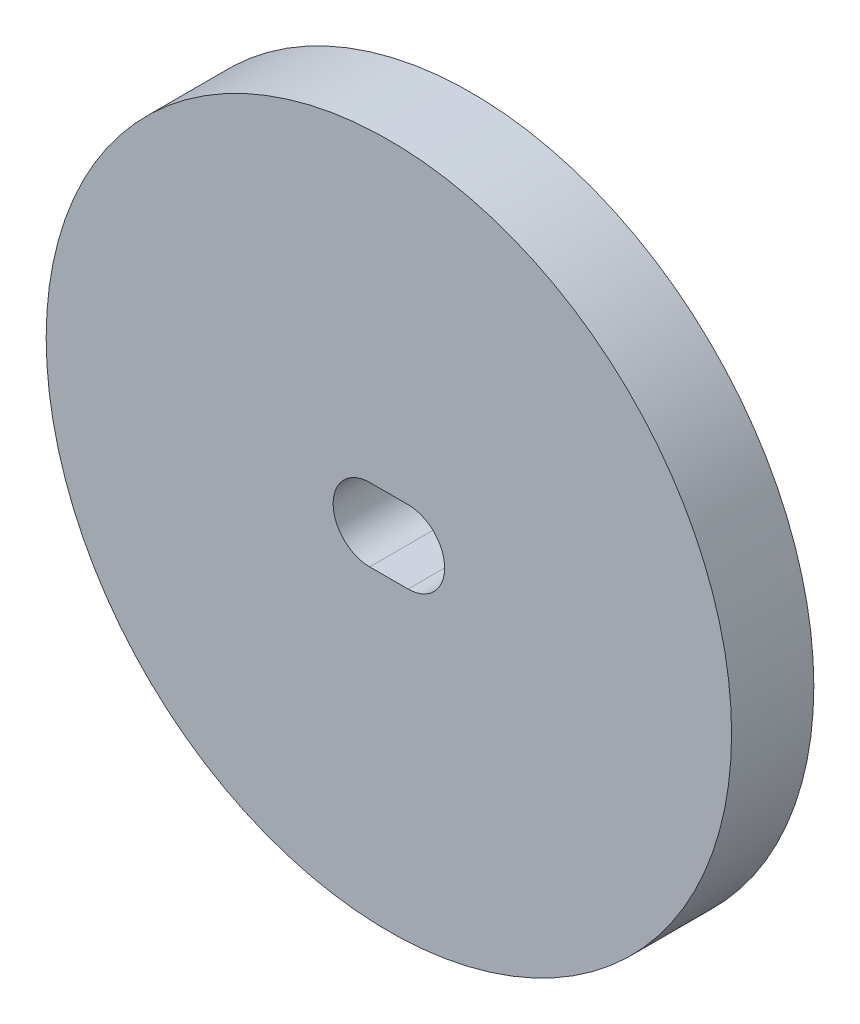
SolidWorks part; units mm, degrees
material "Perspex (TM) GS Acrylic Cast Sheet"
ref_plane "Front Plane" through (0, 0, 0) normal (0, 0, 1) x (1, 0, 0)
ref_plane "Top Plane" through (0, 0, 0) normal (0, 1, 0) x (1, 0, 0)
ref_plane "Right Plane" through (0, 0, 0) normal (1, 0, 0) x (0, 0, -1)
sketch "Sketch1" plane through (0, 0, 0) normal (0, 0, 1) x (1, 0, 0)
  line L0 (-1.05, 0) -> (1.05, 0) construction
  line L1 (-1.05, 2) -> (1.05, 2)
  line L2 (-1.05, -2) -> (1.05, -2)
  circle A0 centre (0, 0) radius 18.75
  arc A1 (-1.05, 2) -> (-1.05, -2) centre (-1.05, 0) ccw
  arc A2 (1.05, -2) -> (1.05, 2) centre (1.05, 0) ccw
  point P4 (0, 0)
  dimension "D1" = 37.5
  dimension "D3" = 2
  dimension "D2" = 2.1
extrude "Boss-Extrude1" add sketch "Sketch1" along normal blind 4.5
sketch "Sketch2" plane through (0, 0, 4.5) normal (0, 0, 1) x (1, 0, 0)
  circle A0 centre (15, 0) radius 3.125
  dimension "D2" = 6.25
  dimension "D1" = 15
